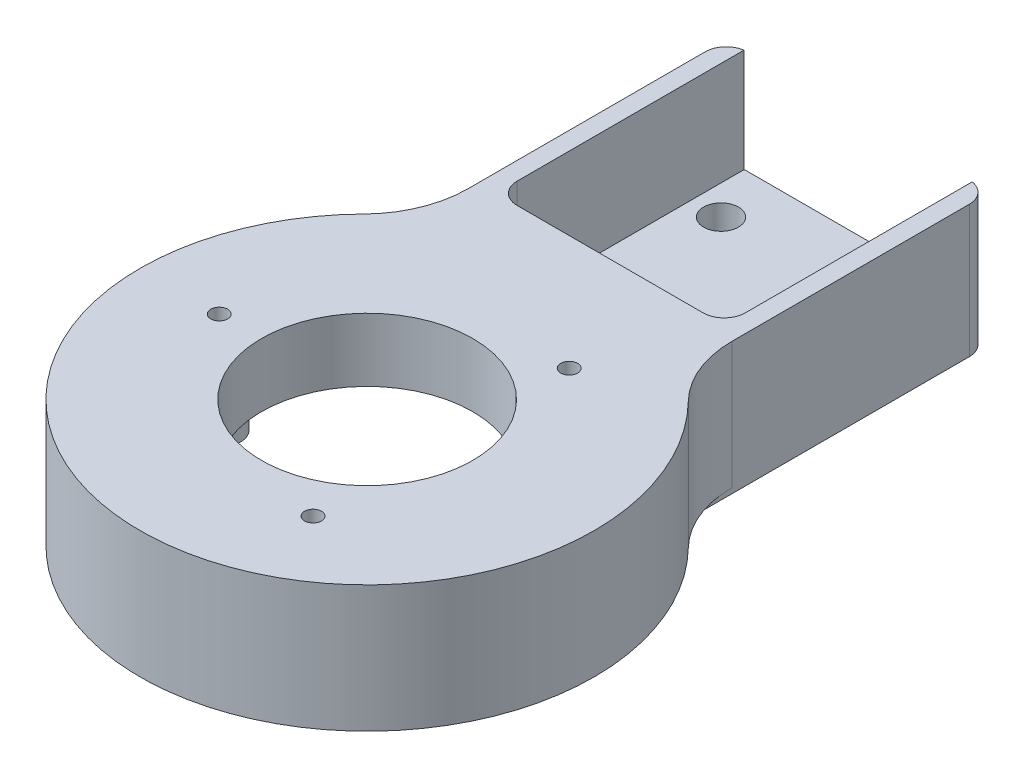
SolidWorks part; units mm, degrees
material "6061-T6 (SS)"
ref_plane "前视基准面" through (0, 0, 0) normal (0, 0, 1) x (1, 0, 0)
ref_plane "上视基准面" through (0, 0, 0) normal (0, 1, 0) x (1, 0, 0)
ref_plane "右视基准面" through (0, 0, 0) normal (1, 0, 0) x (0, 0, -1)
other "Configuration Table"
sketch "草图1" plane through (0, 0, 0) normal (0, 1, 0) x (1, 0, 0)
  circle A0 centre (0, 0) radius 21.5
  dimension "D1" = 43
extrude "凸台-拉伸1" add sketch "草图1" along normal blind 12
sketch "草图3" plane through (0, 12, 0) normal (0, 1, 0) x (1, 0, 0)
  line L0 (0, 21.5) -> (0, 46.5) construction
  line L1 (-12.5, 46.5) -> (12.5, 46.5)
  line L2 (12.5, 46.5) -> (12.5, 17.4929)
  line L3 (-12.5, 46.5) -> (-12.5, 17.4929)
  circle A0 centre (0, 0) radius 21.5 construction
  arc A1 (12.5, 17.4929) -> (-12.5, 17.4929) centre (0, 0) ccw
  dimension "D1" = 12.5
  dimension "D2" = 25
extrude "凸台-拉伸2" add sketch "草图3" against normal blind 13.5
fillet "圆角1" radius 10 2 edges at (12.5, 6, -17.4929) (-12.5, 6, -17.4929)
sketch "草图4" plane through (0, 0, 0) normal (0, -1, 0) x (-1, 0, 0)
  circle A0 centre (0, 0) radius 20
  dimension "D1" = 40
extrude "切除-拉伸1" cut sketch "草图4" against normal blind 6
sketch "草图5" plane through (0, 6, 0) normal (0, -1, 0) x (-1, 0, 0)
  circle A0 centre (0, 0) radius 10
  dimension "D1" = 20
extrude "切除-拉伸2" cut sketch "草图5" against normal blind 6
sketch "草图6" plane through (0, 6, 0) normal (0, -1, 0) x (-1, 0, 0)
  line L0 (0, 0) -> (14, 0) construction
  line L1 (0, 0) -> (12.1244, 7) construction
  circle A0 centre (0, 0) radius 14 construction
  circle A1 centre (14, 0) radius 2
  circle A2 centre (-7, -12.1244) radius 2
  circle A3 centre (-7, 12.1244) radius 2
  point P13 (0, 0)
  dimension "D1" = 28
  dimension "D3" = 4
  dimension "D2" = 30
  dimension "D4" = 3
extrude "凸台-拉伸3" add sketch "草图6" along normal blind 3.5
hole_wizard "M2 螺纹孔的螺纹孔钻头1" positions "3D草图1" profile "草图7" hole size "M2" standard "ISO" end condition through all
sketch3d "3D草图1"
  line L0 (7, 2.5, 12.1244) -> (7, 6, 12.1244) construction
  line L1 (7, 2.5, -12.1244) -> (7, 6, -12.1244) construction
  line L2 (-14, 2.5, 0) -> (-14, 6, 0) construction
  point P0 (7, 2.5, 12.1244)
  point P4 (7, 2.5, -12.1244)
  point P8 (-14, 2.5, 0)
sketch "草图7" plane through (7, 2.5, 12.1244) normal (1, 0, 0) x (0, 0, -1)
  line L0 (0, 0) -> (0, 9.5)
  line L1 (0, 9.5) -> (0.8, 9.5)
  line L2 (0.8, 9.5) -> (0.8, 0.025)
  line L3 (0.8, 0.025) -> (0.825, 0)
  line L5 (0.825, 0) -> (0, 0)
  line L6 (-0.8, 0.025) -> (-0.825, 0) construction
  line L11 (0, -6.35) -> (0, 107.95) construction
  dimension "通孔孔直径" = 1.6
  dimension "通孔孔深度" = 9.5
  dimension "近端锥形沉头孔直径" = 1.65
  dimension "近端锥形沉头孔角度" = 90
sketch "草图8" plane through (0, 0, -46.5) normal (0, 0, -1) x (-1, 0, 0)
  line L0 (-10.8, 12) -> (-10.8, 2.2)
  line L1 (-12.5, 12) -> (12.5, 12) construction
  line L2 (-10.8, 2.2) -> (10.8, 2.2)
  line L3 (10.8, 2.2) -> (10.8, 12)
  line L4 (-12.5, -1.5) -> (12.5, -1.5) construction
  line L5 (-12.5, -1.5) -> (-12.5, 12) construction
  line L6 (12.5, 0) -> (12.5, 12) construction
  dimension "D1" = 3.7
  dimension "D2" = 1.7
  dimension "D3" = 1.7
extrude "切除-拉伸3" cut sketch "草图8" against normal blind 23.5 and the other way through all
fillet "圆角2" radius 2 2 edges at (10.8, 7.1, -23) (-10.8, 7.1, -23)
fillet "圆角3" radius 2 2 edges at (12.5, 5.25, -46.5) (-12.5, 5.25, -46.5)
chamfer "倒角1" distance 1 angle 45 5 edges at (12.5, -1.5, -30.9964) (11.9142, -1.5, -45.9142) (0, -1.5, -46.5) (-11.9142, -1.5, -45.9142) (-12.5, -1.5, -30.9964)
sketch "草图9" plane through (0, 2.2, 0) normal (0, 1, 0) x (1, 0, 0)
  line L0 (-8, 46.5) -> (-8, 41.5) construction
  line L1 (10.5, 46.5) -> (-10.5, 46.5) construction
  line L2 (-8, 41.5) -> (-8, 28.5) construction
  line L4 (0, 46.5) -> (0, 23) construction
  line L5 (8.8, 23) -> (-8.8, 23) construction
  line L6 (8, 41.5) -> (8, 28.5) construction
  line L7 (8, 46.5) -> (8, 41.5) construction
  circle A0 centre (-8, 41.5) radius 1.65
  circle A1 centre (-8, 28.5) radius 1.65
  circle A2 centre (8, 28.5) radius 1.65
  circle A3 centre (8, 41.5) radius 1.65
  dimension "D1" = 5
  dimension "D2" = 13
  dimension "D3" = 16
extrude "切除-拉伸4" cut sketch "草图9" against normal blind 23.5
chamfer "倒角2" distance 1 angle 45 4 edges at (-8, -1.5, -26.85) (-8, -1.5, -39.85) (8, -1.5, -26.85) (8, -1.5, -39.85)
